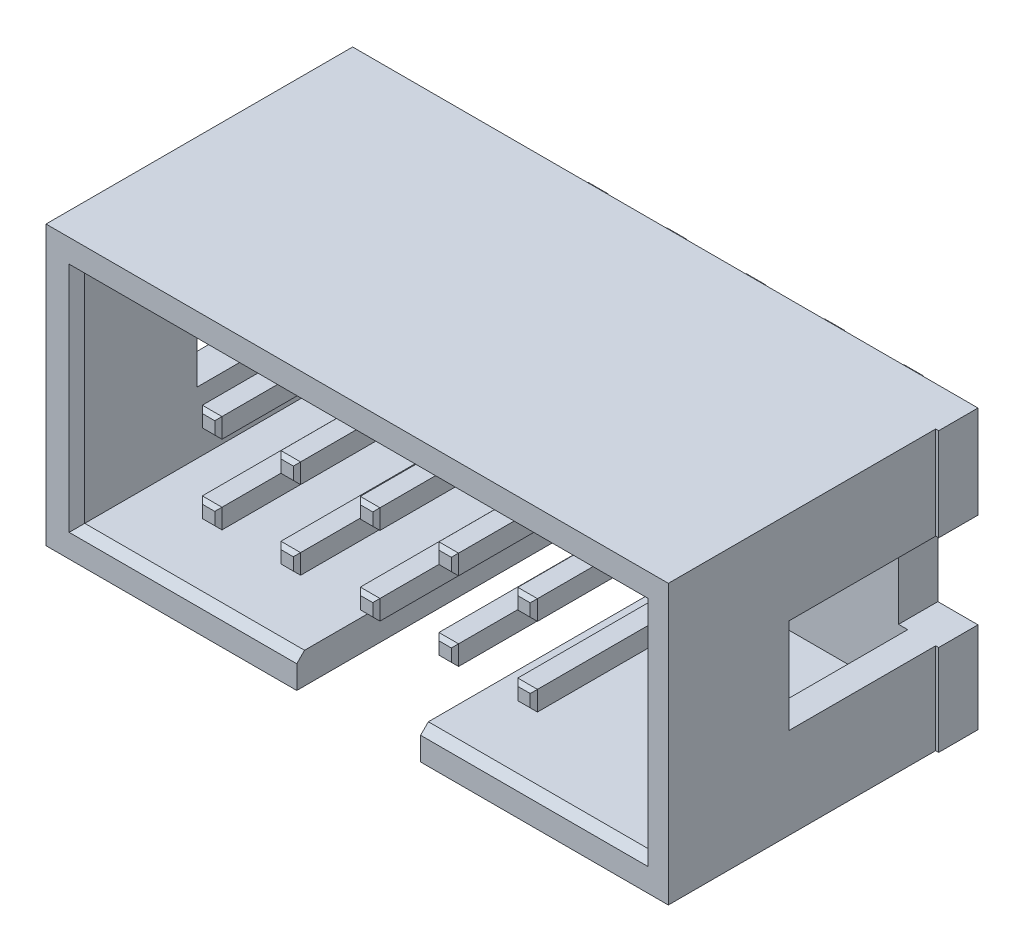
SolidWorks part; units mm, degrees
ref_plane "Alzado" through (0, 0, 0) normal (0, 0, 1) x (1, 0, 0)
ref_plane "Planta" through (0, 0, 0) normal (0, 1, 0) x (1, 0, 0)
ref_plane "Vista lateral" through (0, 0, 0) normal (1, 0, 0) x (0, 0, -1)
sketch "Croquis1" plane through (0, 0, 0) normal (0, 0, 1) x (1, 0, 0)
  line L0 (-1.5558, 0) -> (11.5158, 0) construction
  line L1 (0.3175, -0.3175) -> (-0.3175, -0.3175)
  line L2 (0.3175, -0.3175) -> (0.3175, 0.3175)
  line L3 (0.3175, 0.3175) -> (-0.3175, 0.3175)
  line L4 (-0.3175, -0.3175) -> (-0.3175, 0.3175)
  line L5 (0.3175, -0.3175) -> (-0.3175, 0.3175) construction
  line L6 (0.3175, 0.3175) -> (-0.3175, -0.3175) construction
  line L7 (0, 0) -> (2.5387, 0) construction
  line L8 (2.5387, 0) -> (1.2694, 0) construction
  line L9 (1.2694, 0) -> (1.2694, 0.8609) construction
  line L10 (2.2212, -0.3175) -> (2.2212, 0.3175)
  line L11 (2.2212, -0.3175) -> (2.8562, -0.3175)
  line L12 (2.8562, -0.3175) -> (2.8562, 0.3175)
  line L13 (2.2212, 0.3175) -> (2.8562, 0.3175)
  line L14 (2.5387, 0) -> (3.821, 0) construction
  line L15 (3.821, 0) -> (3.821, 1.1533) construction
  line L16 (5.1033, 0) -> (6.3727, 0) construction
  line L17 (7.6421, 0) -> (5.1033, 0) construction
  line L18 (7.3246, 0.3175) -> (7.9596, -0.3175) construction
  line L19 (7.3246, -0.3175) -> (7.9596, 0.3175) construction
  line L20 (5.4208, 0.3175) -> (4.7858, 0.3175)
  line L21 (4.7858, -0.3175) -> (4.7858, 0.3175)
  line L22 (5.4208, -0.3175) -> (4.7858, -0.3175)
  line L23 (5.4208, -0.3175) -> (5.4208, 0.3175)
  line L24 (7.9596, -0.3175) -> (7.9596, 0.3175)
  line L25 (7.3246, 0.3175) -> (7.9596, 0.3175)
  line L26 (7.3246, -0.3175) -> (7.3246, 0.3175)
  line L27 (7.3246, -0.3175) -> (7.9596, -0.3175)
  line L28 (7.6421, 0) -> (8.9162, 0) construction
  line L29 (8.9162, 0) -> (8.9162, 1.4302) construction
  line L30 (10.5078, -0.3175) -> (9.8728, 0.3175) construction
  line L31 (10.5078, 0.3175) -> (9.8728, -0.3175) construction
  line L32 (10.5078, -0.3175) -> (9.8728, -0.3175)
  line L33 (10.5078, -0.3175) -> (10.5078, 0.3175)
  line L34 (10.5078, 0.3175) -> (9.8728, 0.3175)
  line L35 (9.8728, -0.3175) -> (9.8728, 0.3175)
  line L36 (0, 0) -> (0, -2.3778) construction
  line L37 (0, 0) -> (0, -2.5369) construction
  line L38 (0, -1.2685) -> (-0.9517, -1.2685) construction
  line L39 (0, -2.5369) -> (0, -0.1591) construction
  line L40 (10.5078, -2.8544) -> (9.8728, -2.2194) construction
  line L41 (10.5078, -2.2194) -> (9.8728, -2.8544) construction
  line L42 (8.9162, -2.5369) -> (8.9162, -3.9671) construction
  line L43 (7.6421, -2.5369) -> (8.9162, -2.5369) construction
  line L44 (7.3246, -2.2194) -> (7.9596, -2.8544) construction
  line L45 (7.3246, -2.8544) -> (7.9596, -2.2194) construction
  line L46 (7.6421, -2.5369) -> (5.1033, -2.5369) construction
  line L47 (5.1033, -2.5369) -> (6.3727, -2.5369) construction
  line L48 (3.821, -2.5369) -> (3.821, -3.6902) construction
  line L49 (2.5387, -2.5369) -> (3.821, -2.5369) construction
  line L50 (1.2694, -2.5369) -> (1.2694, -3.3978) construction
  line L51 (2.5387, -2.5369) -> (1.2694, -2.5369) construction
  line L52 (0, -2.5369) -> (2.5387, -2.5369) construction
  line L53 (0.3175, -2.8544) -> (-0.3175, -2.2194) construction
  line L54 (0.3175, -2.2194) -> (-0.3175, -2.8544) construction
  line L55 (-1.5558, -2.5369) -> (11.5158, -2.5369) construction
  line L56 (9.8728, -2.2194) -> (9.8728, -2.8544)
  line L57 (10.5078, -2.8544) -> (9.8728, -2.8544)
  line L58 (10.5078, -2.2194) -> (10.5078, -2.8544)
  line L59 (10.5078, -2.2194) -> (9.8728, -2.2194)
  line L60 (7.3246, -2.2194) -> (7.9596, -2.2194)
  line L61 (7.3246, -2.2194) -> (7.3246, -2.8544)
  line L62 (7.3246, -2.8544) -> (7.9596, -2.8544)
  line L63 (7.9596, -2.2194) -> (7.9596, -2.8544)
  line L64 (5.4208, -2.2194) -> (5.4208, -2.8544)
  line L65 (5.4208, -2.2194) -> (4.7858, -2.2194)
  line L66 (4.7858, -2.2194) -> (4.7858, -2.8544)
  line L67 (5.4208, -2.8544) -> (4.7858, -2.8544)
  line L68 (2.2212, -2.8544) -> (2.8562, -2.8544)
  line L69 (2.8562, -2.2194) -> (2.8562, -2.8544)
  line L70 (2.2212, -2.2194) -> (2.8562, -2.2194)
  line L71 (2.2212, -2.2194) -> (2.2212, -2.8544)
  line L72 (-0.3175, -2.2194) -> (-0.3175, -2.8544)
  line L73 (0.3175, -2.8544) -> (-0.3175, -2.8544)
  line L74 (0.3175, -2.2194) -> (0.3175, -2.8544)
  line L75 (0.3175, -2.2194) -> (-0.3175, -2.2194)
  line L76 (10.1903, 0) -> (10.1903, -2.5369) construction
  line L77 (10.1903, -2.5369) -> (10.1903, -1.2685) construction
  line L78 (10.1903, -1.2685) -> (0, -1.2685) construction
  line L79 (5.0952, -1.2685) -> (5.1033, 0) construction
  line L85 (12.6214, 1.6832) -> (-2.4311, -4.2202) construction
  line L86 (12.6214, -4.2202) -> (-2.4311, 1.6832) construction
  point P0 (0, 0)
  dimension "D1" = 0.635
  dimension "D2" = 0.635
  dimension "D3" = 15.0525
extrude "Saliente-Extruir1" add sketch "Croquis1" along normal blind 9.652 and the other way blind 3.048
chamfer "Chaflán1" distance 0.1166 angle 45 4 edges at (2.2212, 0, 9.652) (2.5387, 0.3175, 9.652) (2.8562, 0, 9.652) (2.5387, -0.3175, 9.652)
chamfer "Chaflán3" distance 0.1166 angle 45 4 edges at (0, -2.2194, 9.652) (-0.3175, -2.5369, 9.652) (0, -2.8544, 9.652) (0.3175, -2.5369, 9.652)
chamfer "Chaflán4" distance 0.1166 angle 45 4 edges at (2.5387, -2.2194, 9.652) (2.2212, -2.5369, 9.652) (2.5387, -2.8544, 9.652) (2.8562, -2.5369, 9.652)
chamfer "Chaflán5" distance 0.1166 angle 45 4 edges at (5.1033, -2.2194, 9.652) (5.4208, -2.5369, 9.652) (5.1033, -2.8544, 9.652) (4.7858, -2.5369, 9.652)
chamfer "Chaflán6" distance 0.1166 angle 45 4 edges at (5.1033, -0.3175, 9.652) (4.7858, 0, 9.652) (5.1033, 0.3175, 9.652) (5.4208, 0, 9.652)
chamfer "Chaflán7" distance 0.1166 angle 45 4 edges at (7.6421, 0.3175, 9.652) (7.9596, 0, 9.652) (7.6421, -0.3175, 9.652) (7.3246, 0, 9.652)
chamfer "Chaflán8" distance 0.1166 angle 45 4 edges at (7.9596, -2.5369, 9.652) (7.6421, -2.2194, 9.652) (7.3246, -2.5369, 9.652) (7.6421, -2.8544, 9.652)
chamfer "Chaflán9" distance 0.1166 angle 45 4 edges at (10.1903, -0.3175, 9.652) (10.5078, 0, 9.652) (10.1903, 0.3175, 9.652) (9.8728, 0, 9.652)
chamfer "Chaflán10" distance 0.1166 angle 45 4 edges at (9.8728, -2.5369, 9.652) (10.1903, -2.8544, 9.652) (10.5078, -2.5369, 9.652) (10.1903, -2.2194, 9.652)
chamfer "Chaflán11" distance 0.1166 angle 45 4 edges at (10.1903, -2.2194, -3.048) (9.8728, -2.5369, -3.048) (10.1903, -2.8544, -3.048) (10.5078, -2.5369, -3.048)
chamfer "Chaflán12" distance 0.1166 angle 45 4 edges at (7.6421, -2.2194, -3.048) (7.9596, -2.5369, -3.048) (7.6421, -2.8544, -3.048) (7.3246, -2.5369, -3.048)
chamfer "Chaflán13" distance 0.1166 angle 45 4 edges at (5.1033, -2.2194, -3.048) (5.4208, -2.5369, -3.048) (4.7858, -2.5369, -3.048) (5.1033, -2.8544, -3.048)
chamfer "Chaflán14" distance 0.1166 angle 45 4 edges at (2.5387, -2.2194, -3.048) (2.2212, -2.5369, -3.048) (2.8562, -2.5369, -3.048) (2.5387, -2.8544, -3.048)
chamfer "Chaflán15" distance 0.1166 angle 45 4 edges at (0, -2.2194, -3.048) (-0.3175, -2.5369, -3.048) (0.3175, -2.5369, -3.048) (0, -2.8544, -3.048)
chamfer "Chaflán16" distance 0.1166 angle 45 4 edges at (10.1903, 0.3175, -3.048) (9.8728, 0, -3.048) (10.1903, -0.3175, -3.048) (10.5078, 0, -3.048)
chamfer "Chaflán17" distance 0.1166 angle 45 4 edges at (7.9596, 0, -3.048) (7.6421, 0.3175, -3.048) (7.6421, -0.3175, -3.048) (7.3246, 0, -3.048)
chamfer "Chaflán18" distance 0.1166 angle 45 4 edges at (5.1033, 0.3175, -3.048) (4.7858, 0, -3.048) (5.4208, 0, -3.048) (5.1033, -0.3175, -3.048)
chamfer "Chaflán19" distance 0.1166 angle 45 4 edges at (2.5387, 0.3175, -3.048) (2.8562, 0, -3.048) (2.2212, 0, -3.048) (2.5387, -0.3175, -3.048)
chamfer "Chaflán20" distance 0.1166 angle 45 4 edges at (0, 0.3175, -3.048) (-0.3175, 0, -3.048) (0, -0.3175, -3.048) (0.3175, 0, -3.048)
chamfer "Chaflán21" distance 0.1166 angle 45 4 edges at (0, -0.3175, 9.652) (-0.3175, 0, 9.652) (0, 0.3175, 9.652) (0.3175, 0, 9.652)
sketch "Croquis2" plane through (0, 0, 0) normal (0, 0, 1) x (1, 0, 0)
  line L0 (5.1033, -0.2009) -> (5.1033, -2.336) construction
  line L1 (4.9024, -0.2009) -> (5.3042, -0.2009) construction
  line L2 (5.3042, -2.336) -> (4.9024, -2.336) construction
  line L3 (5.1033, -1.2685) -> (0.1783, -1.2685) construction
  line L5 (15.2033, 3.2315) -> (-4.9967, 3.2315)
  line L6 (15.2033, 3.2315) -> (15.2033, -5.7685)
  line L7 (15.2033, -5.7685) -> (-4.9967, -5.7685)
  line L8 (-4.9967, 3.2315) -> (-4.9967, -5.7685)
  line L9 (15.2033, 3.2315) -> (-4.9967, -5.7685) construction
  line L10 (15.2033, -5.7685) -> (-4.9967, 3.2315) construction
  dimension "D1" = 20.2
  dimension "D2" = 9
extrude "Saliente-Extruir2" add sketch "Croquis2" along normal blind 1.27
sketch "Croquis3" plane through (0, 0, 1.27) normal (0, 0, 1) x (1, 0, 0)
  line L0 (-4.9967, -3.4037) -> (-3.9967, -3.4037) construction
  line L1 (4.8977, -5.7685) -> (-4.9967, -5.7685)
  line L2 (5.4684, -5.7685) -> (15.2033, -5.7685)
  line L3 (-3.9967, -4.7685) -> (4.8977, -4.7685)
  line L4 (-3.9967, -4.7685) -> (-3.9967, 2.2315)
  line L5 (-3.9967, -5.7685) -> (-3.9967, -4.7685) construction
  line L6 (14.2033, 3.2315) -> (14.2033, 2.2315) construction
  line L7 (14.2033, 2.2315) -> (15.2033, 2.2315) construction
  line L8 (4.8977, -4.7685) -> (4.8977, -5.7685)
  line L9 (-3.9967, 2.2315) -> (14.2033, 2.2315)
  line L10 (14.2033, 2.2315) -> (14.2033, -4.7685)
  line L11 (14.2033, -4.7685) -> (13.9654, -4.7685)
  line L12 (15.2033, -5.7685) -> (15.2033, 3.2315)
  line L13 (15.2033, 3.2315) -> (-4.9967, 3.2315)
  line L14 (15.2033, 3.2315) -> (15.2033, -5.7685)
  line L15 (15.2033, 3.2315) -> (15.1067, 3.3547)
  line L16 (-4.9967, 3.2315) -> (-4.9967, -5.7685)
  line L17 (13.9654, -4.7685) -> (5.4684, -4.7685)
  line L18 (5.4684, -4.7685) -> (5.4684, -5.7685)
  line L19 (-4.9967, 3.2315) -> (-4.9967, -5.7685)
  line L20 (4.8977, -5.7685) -> (-4.9967, -5.7685)
  line L21 (-4.9967, 3.2315) -> (15.2033, 3.2315)
  line L22 (-4.9967, 3.2315) -> (15.1067, 3.3547)
  line L23 (-4.9967, 3.2315) -> (-4.9967, -5.7685)
  line L24 (4.8977, -5.7685) -> (-4.9967, -5.7685)
  line L25 (-4.9967, 3.2315) -> (15.2033, 3.2315)
  line L27 (15.2033, 3.2315) -> (-4.9967, 3.2315)
  line L28 (15.2033, 3.2315) -> (15.2033, -5.7685)
  line L29 (15.2033, -5.7685) -> (-4.9967, -5.7685)
  line L30 (-4.9967, 3.2315) -> (-4.9967, -5.7685)
  line L31 (15.1067, 3.2315) -> (-4.9967, 3.2315)
  line L32 (15.1067, 3.2315) -> (15.1067, -5.7685)
  line L33 (15.1067, -5.7685) -> (-4.9967, -5.7685)
  line L34 (-4.9967, 3.2315) -> (-4.9967, -5.7685)
  line M41 (-4.9967, 3.2315) -> (-4.9967, -5.7685)
  line M42 (-4.9967, -5.7685) -> (15.2033, -5.7685)
  dimension "D1" = 1
  dimension "D2" = 1
  dimension "D3" = 1
  dimension "D4" = 1
extrude "Saliente-Extruir4" add sketch "Croquis3" along normal blind 8.636 contours L32 L27 L8 L3 L4 L9 L10 L11 L17 L18 M41 M42
sketch "Croquis4" plane through (0, 0, 9.906) normal (0, 0, 1) x (1, 0, 0)
  line L0 (5.1033, -2.7378) -> (5.1033, -5.7685) construction
  line L1 (4.9024, -2.7378) -> (5.3042, -2.7378) construction
  line L2 (4.8977, -5.7685) -> (5.4684, -5.7685) construction
  line L3 (5.4684, -5.2685) -> (4.8977, -5.2685) construction
  line L4 (5.4684, -4.7685) -> (5.4684, -5.7685) construction
  line L5 (4.8977, -4.7685) -> (4.8977, -5.7685) construction
  line L6 (5.4684, -5.7685) -> (15.1067, -5.7685) construction
  line L7 (3.1033, -4.7685) -> (7.1033, -4.7685)
  line L8 (3.1033, -4.7685) -> (3.1033, -5.7685)
  line L9 (3.1033, -5.7685) -> (7.1033, -5.7685)
  line L10 (7.1033, -4.7685) -> (7.1033, -5.7685)
  line L11 (3.1033, -4.7685) -> (7.1033, -5.7685) construction
  line L12 (3.1033, -5.7685) -> (7.1033, -4.7685) construction
  point P12 (5.1033, -5.2685)
  dimension "D1" = 4
extrude "Cortar-Extruir1" cut sketch "Croquis4" against normal blind 8.9408
chamfer "Chaflán22" distance 0.2517 angle 45 5 edges at (10.6533, -4.7685, 9.906) (14.2033, -1.2685, 9.906) (5.1033, 2.2315, 9.906) (-3.9967, -1.2685, 9.906) (-0.4467, -4.7685, 9.906)
sketch "Croquis5" plane through (15.1067, 0, 0) normal (1, 0, 0) x (0, 0, -1)
  line L0 (0, -1.2685) -> (-9.906, -1.2685) construction
  line L1 (0, -5.7685) -> (0, 3.2315) construction
  line L2 (-9.906, 3.2315) -> (-9.906, -5.7685) construction
sketch "Croquis6" plane through (15.1067, 0, 0) normal (1, 0, 0) x (0, 0, -1)
  line L0 (0, 1.6584) -> (-6.0079, 1.6584) construction
  line L1 (0, -5.7685) -> (0, 3.2315) construction
  line L2 (-6.0079, 1.6584) -> (-6.0079, -5.7685) construction
  line L3 (-9.906, -5.7685) -> (-1.27, -5.7685) construction
  line L4 (0, -1.2685) -> (0, 0.2322) construction
  line L5 (0, 0.3175) -> (0, -0.3175) construction
  line L6 (0, 0.2322) -> (-6.0079, 0.2322) construction
  line L8 (-6.0079, 0.2322) -> (0, 0.2322)
  line L9 (-6.0079, 0.2322) -> (-6.0079, -2.8337)
  line L10 (-6.0079, -2.8337) -> (0, -2.8337)
  line L11 (0, 0.2322) -> (0, -2.8337)
extrude "Cortar-Extruir2" cut sketch "Croquis6" against normal blind 1.2
sketch "Croquis7" plane through (15.2033, 0, 0) normal (1, 0, 0) x (0, 0, -1)
  line L0 (0, -5.7685) -> (0, 3.2315) construction
  line L1 (-1.27, -2.8337) -> (0, -2.8337)
  line L2 (-1.27, -2.8337) -> (-1.27, 0.2341)
  line L3 (-1.27, 0.2341) -> (0, 0.2341)
  line L4 (0, -2.8337) -> (0, 0.2341)
extrude "Cortar-Extruir3" cut sketch "Croquis7" against normal blind 1.2
sketch "Croquis8" plane through (-4.9967, 0, 0) normal (-1, 0, 0) x (0, 0, 1)
  line L0 (5.2307, -1.2685) -> (5.2307, 0.2327) construction
  line L1 (0, -1.2685) -> (9.906, -1.2685) construction
  line L2 (5.2307, -1.2685) -> (5.2307, -2.7696) construction
  line L3 (5.2307, -2.7696) -> (0, -2.7696) construction
  line L4 (0, 3.2315) -> (0, -5.7685) construction
  line L5 (0, -2.7696) -> (6.0352, -2.7696) construction
  line L6 (0, 0.3175) -> (0, -0.3175) construction
  line L7 (6.0352, -2.7696) -> (0, -2.7696)
  line L8 (6.0352, -2.7696) -> (6.0352, 0.2327)
  line L9 (6.0352, 0.2327) -> (0, 0.2327)
  line L10 (0, -2.7696) -> (0, 0.2327)
extrude "Cortar-Extruir4" cut sketch "Croquis8" against normal blind 1.2
